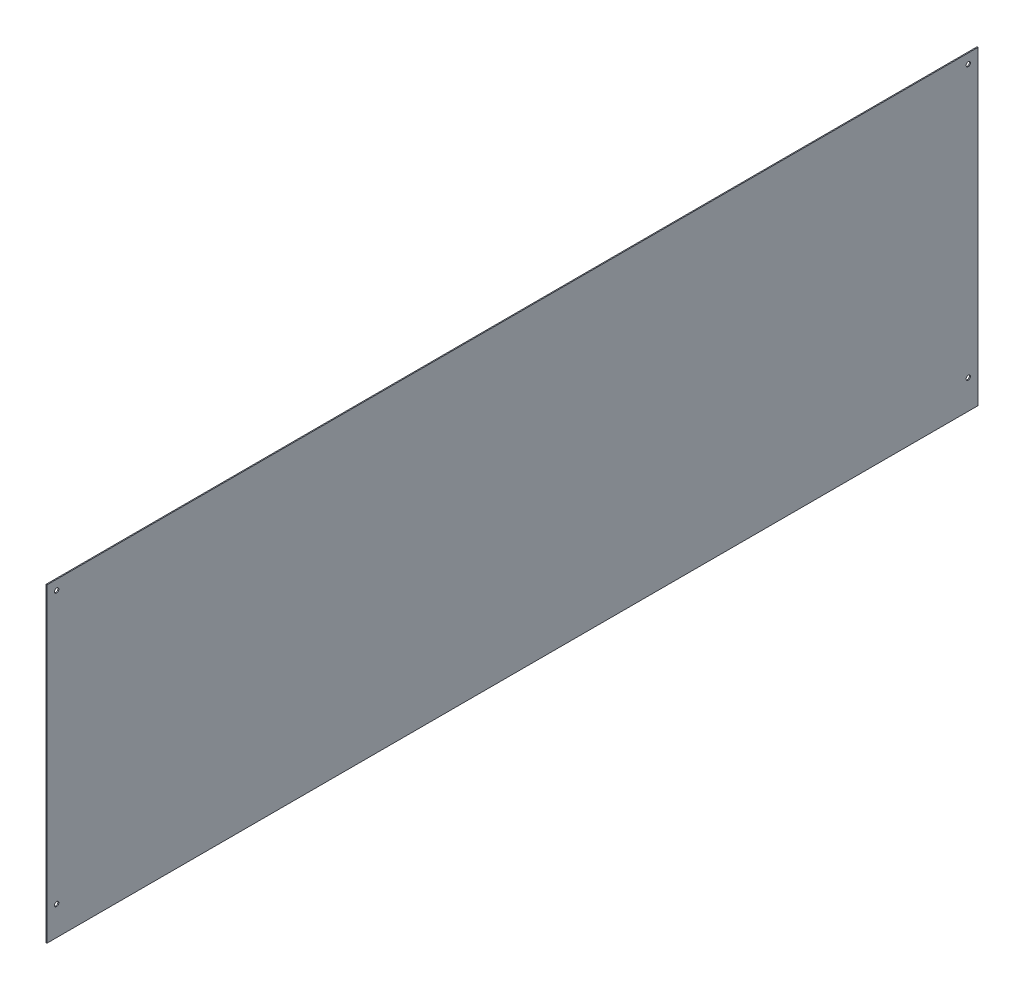
SolidWorks part; units mm, degrees
ref_plane "Front Plane" through (0, 0, 0) normal (0, 0, 1) x (1, 0, 0)
ref_plane "Top Plane" through (0, 0, 0) normal (0, 1, 0) x (1, 0, 0)
ref_plane "Right Plane" through (0, 0, 0) normal (1, 0, 0) x (0, 0, -1)
sketch "Sketch1" plane through (0, 0, 0) normal (1, 0, 0) x (0, 0, -1)
  line L1 (-960, -320) -> (960, -320)
  line L2 (-960, -320) -> (-960, 320)
  line L3 (-960, 320) -> (960, 320)
  line L4 (960, -320) -> (960, 320)
  line L5 (-960, -320) -> (960, 320) construction
  line L6 (-960, 320) -> (960, -320) construction
  circle A0 centre (-940, 300) radius 4.5
  circle A1 centre (940, 300) radius 4.5
  circle A2 centre (940, -260) radius 4.5
  circle A3 centre (-940, -260) radius 4.5
  dimension "D3" = 9
  dimension "D1" = 1920
  dimension "D2" = 640
  dimension "D4" = 20
  dimension "D5" = 20
  dimension "D6" = 60
  dimension "D7" = 20
surface "Surface-Plane1" sketch "Sketch1"
thicken "Thicken1" surfaces to thicken 101 thickness 2 parameters "D1"=2
